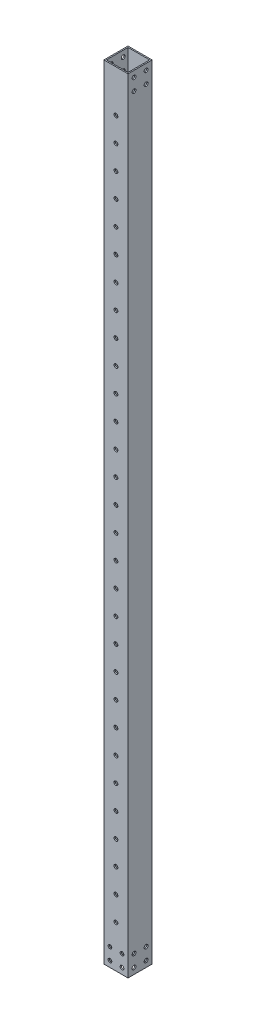
SolidWorks part; units mm, degrees
ref_plane "前视基准面" through (0, 0, 0) normal (0, 0, 1) x (1, 0, 0)
ref_plane "上视基准面" through (0, 0, 0) normal (0, 1, 0) x (1, 0, 0)
ref_plane "右视基准面" through (0, 0, 0) normal (1, 0, 0) x (0, 0, -1)
other "Configuration Table"
sketch "草图1" plane through (0, 0, 0) normal (0, 1, 0) x (1, 0, 0)
  line L1 (-10, -10) -> (10, -10)
  line L2 (-10, -10) -> (-10, 10)
  line L3 (-10, 10) -> (10, 10)
  line L4 (10, -10) -> (10, 10)
  line L5 (-10, -10) -> (10, 10) construction
  line L6 (-10, 10) -> (10, -10) construction
  point P0 (0, 0)
  dimension "D1" = 20
  dimension "D2" = 20
extrude "拉伸-薄壁1" add sketch "草图1" along normal blind 650 thin thin type one direction reverse wall 1
sketch "草图2" plane through (10, 0, 0) normal (1, 0, 0) x (0, 0, -1)
  line L0 (10, 650) -> (10, 0) construction
  line L1 (-10, 650) -> (10, 650)
  line L2 (-10, 650) -> (-10, 630)
  line L3 (-10, 630) -> (10, 630)
  line L4 (10, 650) -> (10, 630)
  line L6 (-10, 0) -> (10, 0)
  line L7 (-10, 0) -> (-10, 20)
  line L8 (-10, 20) -> (10, 20)
  line L9 (10, 0) -> (10, 20)
  dimension "D1" = 20
  dimension "D2" = 20
sketch "草图3" plane through (10, 0, 0) normal (1, 0, 0) x (0, 0, -1)
  line L0 (-10, 10) -> (10, 10) construction
  line L1 (-10, 0) -> (-10, 20) construction
  line L2 (10, 0) -> (10, 20) construction
  line L3 (0, 20) -> (0, 0) construction
  line L4 (-10, 20) -> (10, 20) construction
  line L5 (10, 325) -> (-10, 325) construction
  line L6 (10, 650) -> (10, 0) construction
  line L7 (-10, 650) -> (-10, 0) construction
  line L8 (0, 630) -> (0, 650) construction
  line L9 (-10, 640) -> (10, 640) construction
  circle A0 centre (-5, 15) radius 1.6
  circle A1 centre (-5, 5) radius 1.6
  circle A2 centre (5, 5) radius 1.6
  circle A3 centre (5, 15) radius 1.6
  circle A4 centre (5, 635) radius 1.6
  circle A5 centre (5, 645) radius 1.6
  circle A6 centre (-5, 645) radius 1.6
  circle A7 centre (-5, 635) radius 1.6
  dimension "D1" = 3.2
  dimension "D2" = 5
  dimension "D3" = 5
extrude "切除-拉伸1" cut sketch "草图3" against normal through all
sketch "草图4" plane through (0, 0, 10) normal (0, 0, 1) x (1, 0, 0)
  line L0 (-10, 0) -> (10, 0) construction
  line L1 (0, 35) -> (0, 0) construction
  circle A0 centre (0, 35) radius 1.6
  circle A1 centre (0, 55) radius 1.6
  circle A2 centre (0, 75) radius 1.6
  circle A3 centre (0, 95) radius 1.6
  circle A4 centre (0, 115) radius 1.6
  circle A5 centre (0, 135) radius 1.6
  circle A6 centre (0, 155) radius 1.6
  circle A7 centre (0, 175) radius 1.6
  circle A8 centre (0, 195) radius 1.6
  circle A9 centre (0, 215) radius 1.6
  circle A10 centre (0, 235) radius 1.6
  circle A11 centre (0, 255) radius 1.6
  circle A12 centre (0, 275) radius 1.6
  circle A13 centre (0, 295) radius 1.6
  circle A14 centre (0, 315) radius 1.6
  circle A15 centre (0, 335) radius 1.6
  circle A16 centre (0, 355) radius 1.6
  circle A17 centre (0, 375) radius 1.6
  circle A18 centre (0, 395) radius 1.6
  circle A19 centre (0, 415) radius 1.6
  circle A20 centre (0, 435) radius 1.6
  circle A21 centre (0, 455) radius 1.6
  circle A22 centre (0, 475) radius 1.6
  circle A23 centre (0, 495) radius 1.6
  circle A24 centre (0, 515) radius 1.6
  circle A25 centre (0, 535) radius 1.6
  circle A26 centre (0, 555) radius 1.6
  circle A27 centre (0, 575) radius 1.6
  circle A28 centre (0, 595) radius 1.6
  circle A29 centre (0, 615) radius 1.6
  dimension "D1" = 3.2
  dimension "D2" = 35
  dimension "D3" = 30
extrude "切除-拉伸2" cut sketch "草图4" against normal through all
sketch "草图5" plane through (0, 0, 10) normal (0, 0, 1) x (1, 0, 0)
  line L0 (10, 0) -> (10, 20) construction
  line L1 (-10, 0) -> (10, 0) construction
  line L2 (-10, 0) -> (-10, 20) construction
  line L3 (-10, 20) -> (10, 20) construction
  line L4 (10, 0) -> (10, 20) construction
  line L5 (10, 0) -> (10, 20) construction
  line L6 (-10, 10) -> (10, 10) construction
  line L7 (0, 20) -> (0, 0) construction
  circle A0 centre (-5, 15) radius 1.55
  circle A1 centre (-5, 5) radius 1.55
  circle A2 centre (5, 5) radius 1.55
  circle A3 centre (5, 15) radius 1.55
  dimension "D1" = 3.1
  dimension "D2" = 5
  dimension "D3" = 5
extrude "切除-拉伸3" cut sketch "草图5" against normal through all
